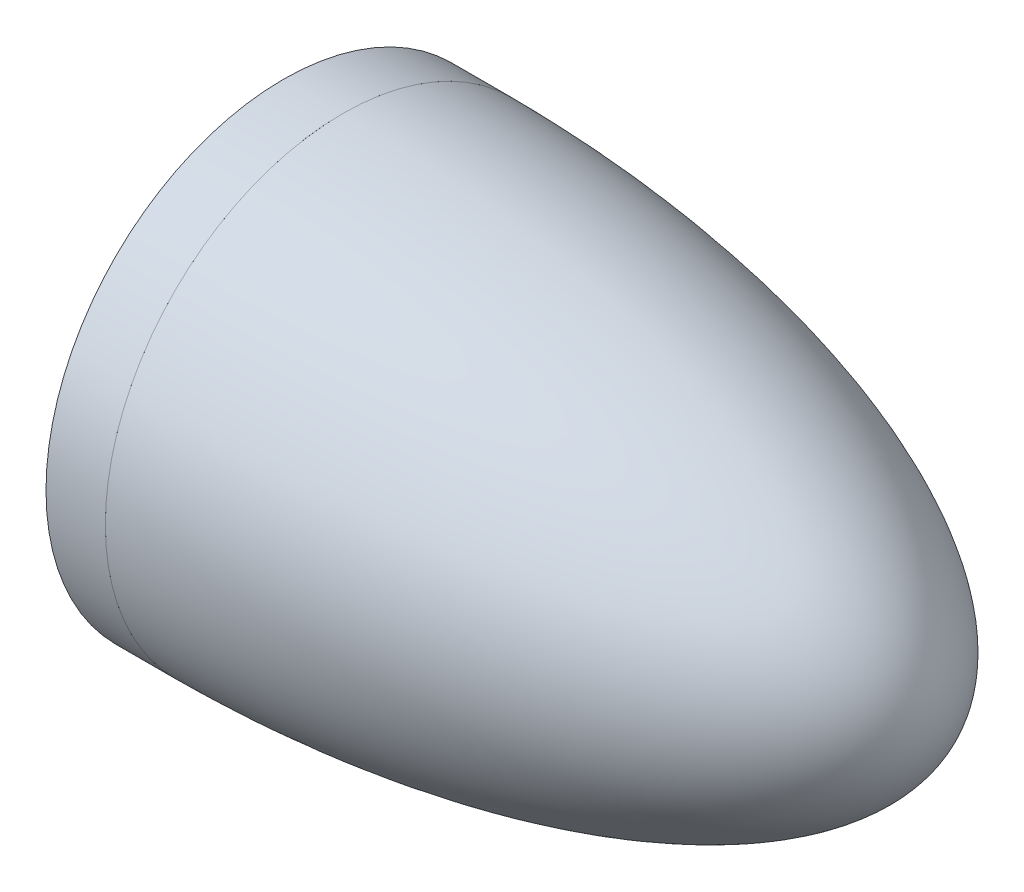
SolidWorks part; units mm, degrees
ref_plane "Front Plane" through (0, 0, 0) normal (0, 0, 1) x (1, 0, 0)
ref_plane "Top Plane" through (0, 0, 0) normal (0, 1, 0) x (1, 0, 0)
ref_plane "Right Plane" through (0, 0, 0) normal (1, 0, 0) x (0, 0, -1)
sketch "Sketch5" plane through (0, 0, 0) normal (0, 0, 1) x (1, 0, 0)
  line L0 (0, 0) -> (51.4986, 0) construction
  line L1 (-0.329, 20) -> (0, 0)
  line L2 (0, 0) -> (49.671, 0)
  spline S0 degree 4 poles (-5.332, 19.8997) (-5.1696, 19.906) (-4.8509, 19.9181) (-4.268, 19.94) (-3.24, 19.9666) (-2.3015, 19.9885) (-0.8946, 20.0003) (-0.0076, 20.0012) (1.1734, 19.9931) (2.0795, 19.9779) (3.088, 19.9552) (4.0399, 19.9248) (5.0232, 19.8869) (5.989, 19.8412) (7.206, 19.7745) (8.6601, 19.6789) (10.3582, 19.5445) (12.2941, 19.359) (14.2277, 19.1408) (16.1566, 18.889) (18.081, 18.6026) (19.9995, 18.2804) (21.9116, 17.9209) (23.8158, 17.5225) (26.1849, 16.9733) (28.5364, 16.3519) (30.8658, 15.6515) (33.6265, 14.7047) (36.1585, 13.7154) (38.6323, 12.5851) (41.0195, 11.2825) (42.9018, 10.0822) (44.3757, 8.9948) (45.6398, 7.904) (46.6883, 6.8386) (47.4897, 5.8773) (48.134, 4.9567) (48.6386, 4.0803) (49.0338, 3.231) (49.3435, 2.3558) (49.5633, 1.448) (49.651, 0.7313) (49.671, 0.2485) (49.671, 0) knots 0 0 0 0 0 0.009997 0.019994 0.039989 0.059983 0.079978 0.095532 0.111087 0.126641 0.142196 0.15775 0.173304 0.188859 0.204413 0.235522 0.266631 0.29774 0.328849 0.359958 0.391067 0.422175 0.453284 0.484393 0.515502 0.57772 0.608829 0.639938 0.702155 0.751534 0.782643 0.813752 0.84486 0.868586 0.889325 0.909267 0.924821 0.940372 0.95393 0.969106 0.98411 1 1 1 1 1 construction
  spline S1 degree 4 poles (-0.329, 20) (-0.1052, 20) (0.3467, 19.9987) (1.1734, 19.9931) (2.0795, 19.9779) (3.088, 19.9552) (4.0399, 19.9248) (5.0232, 19.8869) (5.989, 19.8412) (7.206, 19.7745) (8.6601, 19.6789) (10.3582, 19.5445) (12.2941, 19.359) (14.2277, 19.1408) (16.1566, 18.889) (18.081, 18.6026) (19.9995, 18.2804) (21.9116, 17.9209) (23.8158, 17.5225) (26.1849, 16.9733) (28.5364, 16.3519) (30.8658, 15.6515) (33.6265, 14.7047) (36.1585, 13.7154) (38.6323, 12.5851) (41.0195, 11.2825) (42.9018, 10.0822) (44.3757, 8.9948) (45.6398, 7.904) (46.6883, 6.8386) (47.4897, 5.8773) (48.134, 4.9567) (48.6386, 4.0803) (49.0338, 3.231) (49.3435, 2.3558) (49.5633, 1.448) (49.651, 0.7313) (49.671, 0.2485) (49.671, 0) knots 0.079978 0.079978 0.079978 0.079978 0.079978 0.095532 0.111087 0.126641 0.142196 0.15775 0.173304 0.188859 0.204413 0.235522 0.266631 0.29774 0.328849 0.359958 0.391067 0.422175 0.453284 0.484393 0.515502 0.57772 0.608829 0.639938 0.702155 0.751534 0.782643 0.813752 0.84486 0.868586 0.889325 0.909267 0.924821 0.940372 0.95393 0.969106 0.98411 1 1 1 1 1
revolve "Revolve1" add sketch "Sketch5" angle 360 about L0
sketch "Sketch6" plane through (0, 0, 0) normal (1, 0, 0) x (0, 0, -1)
  circle A0 centre (0, 0) radius 20
extrude "Boss-Extrude6" add sketch "Sketch6" against normal blind 5
sketch "Sketch7" plane through (-5, 0, 0) normal (-1, 0, 0) x (0, 0, 1)
  line L1 (-1.3434, 17.4539) -> (1.1666, 17.4539)
  line L2 (-1.3434, 17.4539) -> (-1.3434, 14.9439)
  line L3 (-1.3434, 14.9439) -> (1.1666, 14.9439)
  line L4 (1.1666, 17.4539) -> (1.1666, 14.9439)
  dimension "D1" = 2.51
  dimension "D2" = 2.51
extrude "Cut-Extrude2" cut sketch "Sketch7" against normal blind 4
